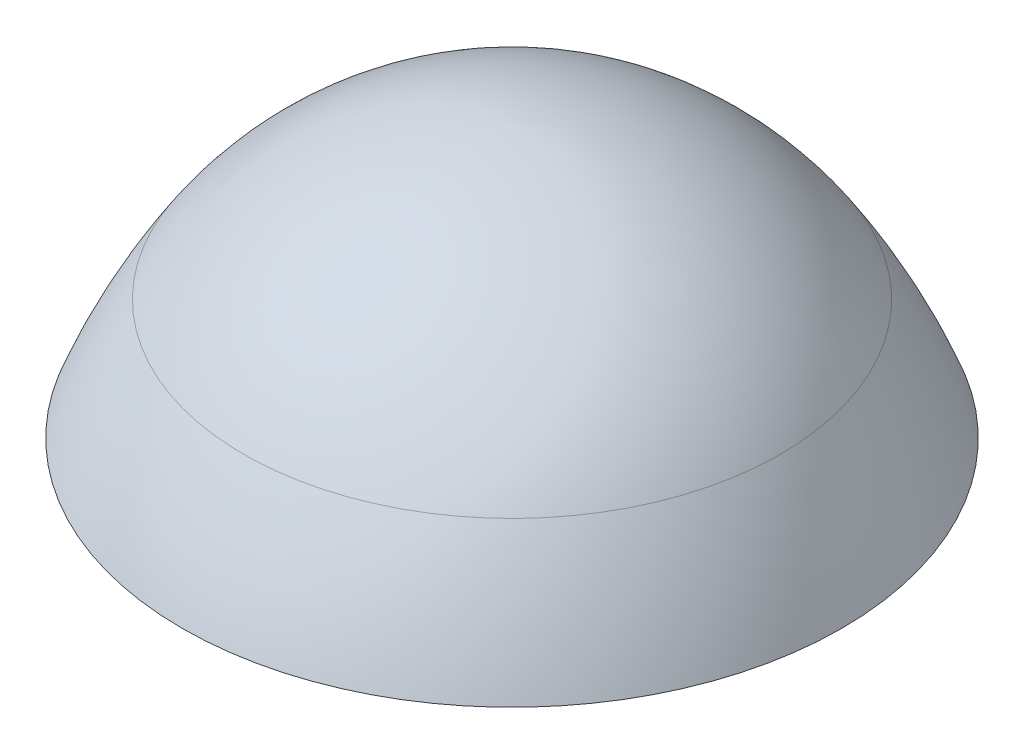
SolidWorks part; units mm, degrees
ref_plane "Front Plane" through (0, 0, 0) normal (0, 0, 1) x (1, 0, 0)
ref_plane "Top Plane" through (0, 0, 0) normal (0, 1, 0) x (1, 0, 0)
ref_plane "Right Plane" through (0, 0, 0) normal (1, 0, 0) x (0, 0, -1)
sketch "Sketch4" plane through (0, 0, 0) normal (1, 0, 0) x (0, 0, -1)
  line L0 (0, 0) -> (-4.5, 0)
  line L1 (0, 0) -> (0, 3.7)
  arc A0 (-4.5, 0) -> (-3.6638, 1.6408) centre (3.6723, -3.1312) cw
  arc A1 (-3.6638, 1.6408) -> (0, 3.7) centre (0.1359, -0.8309) cw
  dimension "D2" = 3.7
  dimension "D1" = 4.5
revolve "Revolve1" add sketch "Sketch4" angle 360 about L1
shell "Shell1" thickness 2
